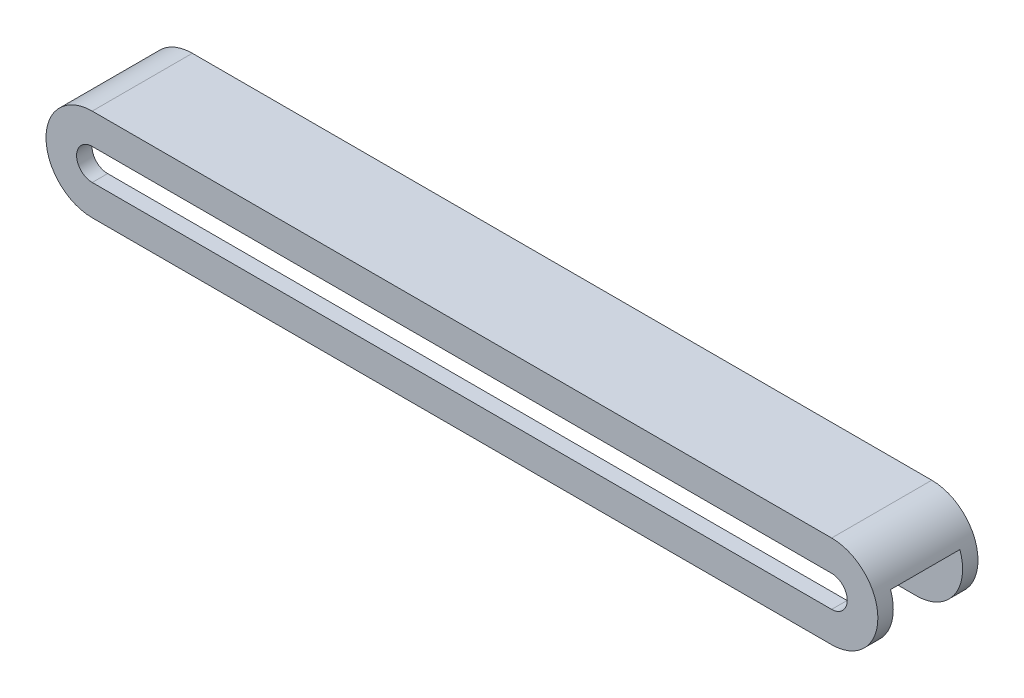
SolidWorks part; units mm, degrees
ref_plane "Front Plane" through (0, 0, 0) normal (0, 0, 1) x (1, 0, 0)
ref_plane "Top Plane" through (0, 0, 0) normal (0, 1, 0) x (1, 0, 0)
ref_plane "Right Plane" through (0, 0, 0) normal (1, 0, 0) x (0, 0, -1)
sketch "Sketch1" plane through (0, 0, 0) normal (0, 0, 1) x (1, 0, 0)
  line L0 (0, 0) -> (304.8, 0) construction
  line L1 (0, 6.4325) -> (304.8, 6.4325)
  line L2 (0, -6.4325) -> (304.8, -6.4325)
  line L3 (0, 0) -> (304.8, 0) construction
  line L4 (0, 19.05) -> (304.8, 19.05)
  line L5 (0, -19.05) -> (304.8, -19.05)
  arc A0 (0, 6.4325) -> (0, -6.4325) centre (0, 0) ccw
  arc A1 (304.8, -6.4325) -> (304.8, 6.4325) centre (304.8, 0) ccw
  arc A2 (0, 19.05) -> (0, -19.05) centre (0, 0) ccw
  arc A3 (304.8, -19.05) -> (304.8, 19.05) centre (304.8, 0) ccw
  point P3 (152.4, 0)
  point P10 (152.4, 0)
  dimension "D1" = 304.8
  dimension "D2" = 12.8651
  dimension "D3" = 38.1
extrude "Boss-Extrude1" add sketch "Sketch1" along normal blind 41.275
sketch "Sketch2" plane through (0, -19.05, 0) normal (0, -1, 0) x (1, 0, 0)
  line L0 (323.85, 0) -> (304.8, 0)
  line L1 (323.85, 0) -> (304.8, 0) construction
  line L2 (304.8, 0) -> (0, 0)
  line L3 (304.8, 0) -> (0, 0) construction
  line L4 (0, 0) -> (-19.05, 0)
  line L5 (304.8, 0) -> (-19.05, 0) construction
  line L6 (-19.05, 0) -> (-19.05, 41.275)
  line L7 (-19.05, 0) -> (-19.05, 41.275) construction
  line L8 (-19.05, 41.275) -> (0, 41.275)
  line L9 (-19.05, 41.275) -> (0, 41.275) construction
  line L10 (0, 41.275) -> (304.8, 41.275)
  line L11 (0, 41.275) -> (323.85, 41.275) construction
  line L12 (304.8, 41.275) -> (323.85, 41.275)
  line L13 (304.8, 41.275) -> (323.85, 41.275) construction
  line L14 (323.85, 41.275) -> (323.85, 0)
  line L15 (323.85, 41.275) -> (323.85, 0) construction
  line L16 (-19.05, 20.6375) -> (323.85, 20.6375) construction
  line L17 (323.85, 6.35) -> (-19.05, 6.35)
  line L18 (323.85, 6.35) -> (323.85, 34.925)
  line L19 (-19.05, 6.35) -> (-19.05, 34.925)
  line L20 (323.85, 34.925) -> (-19.05, 34.925)
  line L21 (323.85, 6.35) -> (-19.05, 34.925) construction
  line L22 (-19.05, 6.35) -> (323.85, 34.925) construction
  point P10 (0, 0)
  point P11 (152.4, 20.6375)
  point P12 (152.4, 20.6375)
  dimension "D1" = 28.575
extrude "Cut-Extrude1" cut sketch "Sketch2" against normal up to surface (25.4825 mm away) up to face at (152.4, 6.4325, 20.6375)
